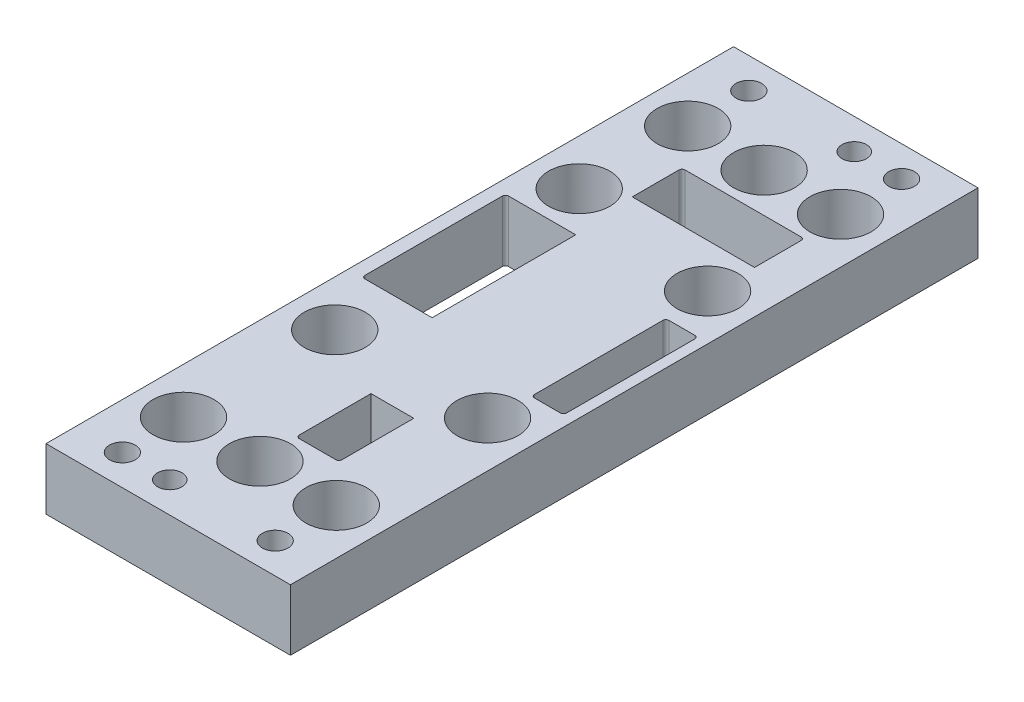
SolidWorks part; units mm, degrees
material "Plain Carbon Steel"
ref_plane "Front Plane" through (0, 0, 0) normal (0, 0, 1) x (1, 0, 0)
ref_plane "Top Plane" through (0, 0, 0) normal (0, 1, 0) x (1, 0, 0)
ref_plane "Right Plane" through (0, 0, 0) normal (1, 0, 0) x (0, 0, -1)
sketch "Sketch1" plane through (0, 0, 0) normal (0, 1, 0) x (1, 0, 0)
  line L0 (-46, 0) -> (34, 0) construction
  line L1 (-46, -112.5) -> (34, -112.5)
  line L2 (-46, -112.5) -> (-46, 112.5)
  line L3 (-46, 112.5) -> (34, 112.5)
  line L4 (34, -112.5) -> (34, 112.5)
  dimension "D1" = 34
  dimension "D2" = 46
  dimension "D3" = 225
extrude "Boss-Extrude1" add sketch "Sketch1" against normal blind 20
sketch "Sketch2" plane through (0, 0, 0) normal (0, 1, 0) x (1, 0, 0)
  line L0 (18, -9.64) -> (29.5, -9.64) construction
  line L1 (29.5, 14.36) -> (18, 14.36) construction
  line L2 (30.5, -8.64) -> (30.5, 13.36) construction
  line L3 (20, -9.64) -> (29.5, -9.64) construction
  line L4 (29.5, 14.36) -> (20, 14.36) construction
  line L5 (30.5, -8.64) -> (30.5, 13.36) construction
  line L6 (20, 14.36) -> (20, -9.64) construction
  line L7 (22, -9.64) -> (22, 14.36) construction
  line L9 (21, -19.64) -> (29.5, -19.64)
  line L10 (20, -18.64) -> (20, 23.36)
  line L11 (21, 24.36) -> (29.5, 24.36)
  line L12 (30.5, -18.64) -> (30.5, 23.36)
  arc A0 (29.5, -9.64) -> (30.5, -8.64) centre (29.5, -8.64) ccw construction
  arc A1 (30.5, 13.36) -> (29.5, 14.36) centre (29.5, 13.36) ccw construction
  arc A2 (29.5, -9.64) -> (30.5, -8.64) centre (29.5, -8.64) ccw construction
  arc A3 (30.5, 13.36) -> (29.5, 14.36) centre (29.5, 13.36) ccw construction
  arc A4 (21, -19.64) -> (20, -18.64) centre (21, -18.64) cw
  arc A5 (29.5, -19.64) -> (30.5, -18.64) centre (29.5, -18.64) ccw
  arc A6 (29.5, 24.36) -> (30.5, 23.36) centre (29.5, 23.36) cw
  arc A7 (20, 23.36) -> (21, 24.36) centre (21, 23.36) cw
  dimension "D6" = 1
  dimension "D1" = 2
  dimension "D2" = 10.5
  dimension "D3" = 24
  dimension "D4" = 10
  dimension "D5" = 10
extrude "Cut-Extrude1" cut sketch "Sketch2" against normal up to next
sketch "Sketch4" plane through (0, 0, 0) normal (0, 1, 0) x (1, 0, 0)
  line L0 (7, -68.64) -> (7, -43.14) construction
  line L2 (-7, -43.14) -> (-7, -68.64) construction
  line L3 (-6, -69.64) -> (6, -69.64) construction
  line L4 (7, -68.64) -> (7, -45.14)
  line L5 (7, -45.14) -> (-7, -45.14)
  line L6 (-7, -45.14) -> (-7, -68.64)
  line L7 (-6, -69.64) -> (6, -69.64)
  line L8 (-7, -47.14) -> (7, -47.14) construction
  arc A2 (-7, -68.64) -> (-6, -69.64) centre (-6, -68.64) ccw construction
  arc A3 (6, -69.64) -> (7, -68.64) centre (6, -68.64) ccw construction
  arc A6 (-7, -68.64) -> (-6, -69.64) centre (-6, -68.64) ccw
  arc A7 (6, -69.64) -> (7, -68.64) centre (6, -68.64) ccw
  dimension "D1" = 2
extrude "Cut-Extrude2" cut sketch "Sketch4" against normal up to next
sketch "Sketch5" plane through (0, 0, 0) normal (0, 1, 0) x (1, 0, 0)
  line L1 (-16.5, 33.36) -> (-40.5, 33.36) construction
  line L2 (-41.5, 32.36) -> (-41.5, -12.64) construction
  line L3 (-40.5, -13.64) -> (-16.5, -13.64) construction
  line L4 (-18.5, -13.64) -> (-18.5, 33.36)
  line L5 (-18.5, 33.36) -> (-40.5, 33.36)
  line L6 (-41.5, 32.36) -> (-41.5, -12.64)
  line L7 (-40.5, -13.64) -> (-18.5, -13.64)
  line L8 (-20.5, 33.36) -> (-20.5, -13.64) construction
  arc A2 (-40.5, 33.36) -> (-41.5, 32.36) centre (-40.5, 32.36) ccw construction
  arc A3 (-41.5, -12.64) -> (-40.5, -13.64) centre (-40.5, -12.64) ccw construction
  arc A6 (-40.5, 33.36) -> (-41.5, 32.36) centre (-40.5, 32.36) ccw
  arc A7 (-41.5, -12.64) -> (-40.5, -13.64) centre (-40.5, -12.64) ccw
  dimension "D1" = 2
extrude "Cut-Extrude3" cut sketch "Sketch5" against normal up to next
sketch "Sketch6" plane through (0, 0, 0) normal (0, 1, 0) x (1, 0, 0)
  line L0 (19, 69.64) -> (-19, 69.64) construction
  line L1 (-20, 68.64) -> (-20, 51.36) construction
  line L3 (20, 51.36) -> (20, 68.64) construction
  line L4 (19, 69.64) -> (-19, 69.64)
  line L5 (-20, 68.64) -> (-20, 53.36)
  line L6 (-20, 53.36) -> (20, 53.36)
  line L7 (20, 53.36) -> (20, 68.64)
  line L8 (-20, 55.36) -> (20, 55.36) construction
  arc A0 (20, 68.64) -> (19, 69.64) centre (19, 68.64) ccw construction
  arc A1 (-19, 69.64) -> (-20, 68.64) centre (-19, 68.64) ccw construction
  arc A4 (20, 68.64) -> (19, 69.64) centre (19, 68.64) ccw
  arc A5 (-19, 69.64) -> (-20, 68.64) centre (-19, 68.64) ccw
  dimension "D1" = 2
extrude "Cut-Extrude4" cut sketch "Sketch6" against normal up to next
hole_wizard "CBORE for M8 Hex Socket Head Cap Screw1" positions "Sketch10" profile "Sketch9" counterbore size "M8" standard "ISO" end condition through all
sketch "Sketch10" plane through (0, -20, 0) normal (0, -1, 0) x (-1, 0, 0)
  line L0 (-34, 112.5) -> (46, 112.5) construction
  line L1 (-34, -112.5) -> (-34, 112.5) construction
  line L2 (46, 112.5) -> (46, -112.5) construction
  line L3 (46, -112.5) -> (-34, -112.5) construction
  point P0 (-19, 102.5)
  point P2 (31, 102.5)
  point P4 (-19, -102.5)
  point P6 (31, -102.5)
  dimension "D1" = 10
  dimension "D2" = 15
  dimension "D3" = 15
  dimension "D4" = 10
sketch "Sketch9" plane through (19, -20, -102.5) normal (1, 0, 0) x (0, 0, -1)
  line L0 (0, 0) -> (0, 20)
  line L1 (0, 20) -> (4.2, 20)
  line L3 (4.2, 20) -> (4.2, 8.6)
  line L4 (4.2, 8.6) -> (7.5, 8.6)
  line L5 (7.5, 8.6) -> (7.5, 0)
  line L7 (7.5, 0) -> (0, 0)
  line L11 (0, -6.35) -> (0, 107.95) construction
  dimension "Thru Hole Dia." = 8.4
  dimension "Thru Hole Depth" = 20
  dimension "C'Bore Dia." = 15
  dimension "C'Bore Depth" = 8.6
hole_wizard "Ø8.0mm Dowel Hole1" positions "Sketch13" profile "Sketch12" hole size "Ø8.0" standard "ISO" end condition through all
sketch "Sketch13" plane through (0, -20, 0) normal (0, -1, 0) x (-1, 0, 0)
  line L0 (-34, 112.5) -> (46, 112.5) construction
  line L1 (46, -112.5) -> (-34, -112.5) construction
  circle A0 centre (-19, 102.5) radius 7.5 construction
  circle A1 centre (31, -102.5) radius 7.5 construction
  point P0 (-3.5, 102.5)
  point P2 (15.5, -102.5)
  dimension "D1" = 8
  dimension "D3" = 8
  dimension "D2" = 10
  dimension "D4" = 10
sketch "Sketch12" plane through (3.5, -20, -102.5) normal (1, 0, 0) x (0, 0, -1)
  line L0 (0, 0) -> (0, 20)
  line L1 (0, 20) -> (4, 20)
  line L2 (4, 20) -> (4, 0)
  line L5 (4, 0) -> (0, 0)
  line L11 (0, -6.35) -> (0, 107.95) construction
  dimension "Thru Hole Dia." = 8
  dimension "Thru Hole Depth" = 20
sketch "Sketch7" plane through (0, 0, 0) normal (0, 1, 0) x (1, 0, 0)
  line L0 (-46, 112.5) -> (-46, -112.5) construction
  line L1 (34, -112.5) -> (34, 112.5) construction
  line L2 (-6, 112.5) -> (-6, -112.5) construction
  line L3 (34, 112.5) -> (-46, 112.5) construction
  line L4 (-46, -112.5) -> (34, -112.5) construction
  line L5 (-46, 0) -> (34, 0) construction
  circle A1 centre (-31, -33) radius 10
  circle A2 centre (-6, 82.5) radius 10
  circle A3 centre (19, -33) radius 10
  circle A4 centre (-31, 47) radius 10
  circle A5 centre (19, 39) radius 10
  circle A7 centre (-31, -82.5) radius 10
  circle A8 centre (-6, -82.5) radius 10
  circle A10 centre (19, -82.5) radius 10
  circle A11 centre (-31, 82.5) radius 10
  circle A14 centre (19, 82.5) radius 10
  dimension "D1" = 15
  dimension "D9" = 20
  dimension "D2" = 15
  dimension "D3" = 30
  dimension "D4" = 30
  dimension "D5" = 47
  dimension "D6" = 39
  dimension "D8" = 33
extrude "Cut-Extrude5" cut sketch "Sketch7" against normal up to next
